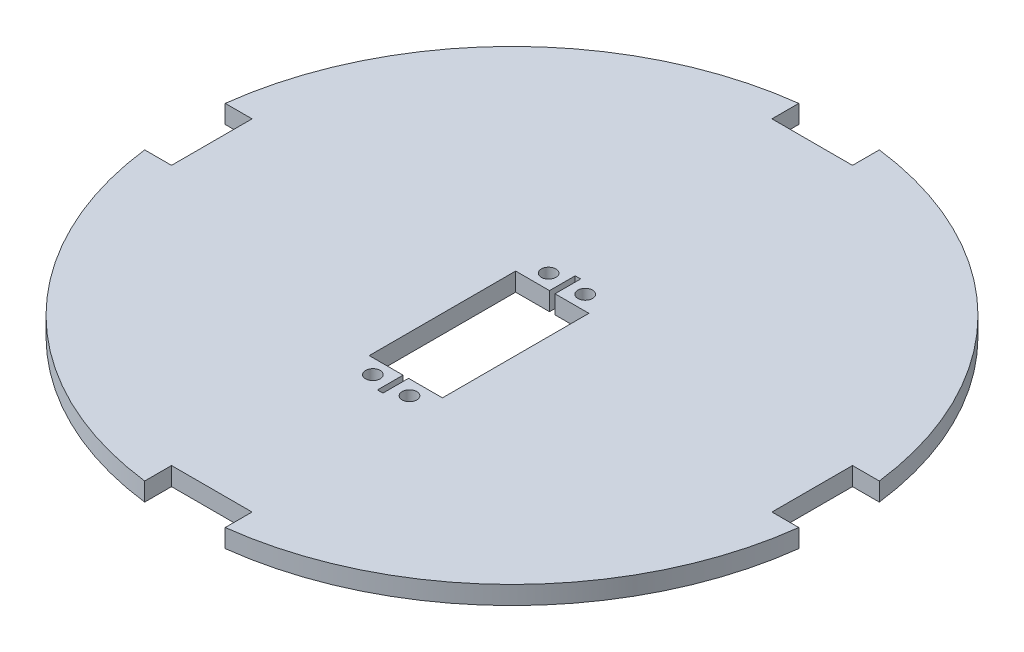
SolidWorks part; units mm, degrees
material "Balsa"
ref_plane "Front Plane" through (0, 0, 0) normal (0, 0, 1) x (1, 0, 0)
ref_plane "Top Plane" through (0, 0, 0) normal (0, 1, 0) x (1, 0, 0)
ref_plane "Right Plane" through (0, 0, 0) normal (1, 0, 0) x (0, 0, -1)
sketch "Sketch1" plane through (0, 0, 0) normal (0, 1, 0) x (1, 0, 0)
  circle A0 centre (0, 0) radius 90
  dimension "D1" = 180
extrude "Boss-Extrude1" add sketch "Sketch1" along normal blind 5
sketch "Sketch2" plane through (0, 5, 0) normal (0, 1, 0) x (1, 0, 0)
  line L1 (-11, 82) -> (11, 82)
  line L2 (-11, 82) -> (-11, 107.4856)
  line L3 (-11, 107.4856) -> (11, 107.4856)
  line L4 (11, 82) -> (11, 107.4856)
  line L5 (-11, 82) -> (11, 107.4856) construction
  line L6 (-11, 107.4856) -> (11, 82) construction
  point P0 (0, 94.7428)
  dimension "D1" = 82
  dimension "D2" = 22
extrude "Cut-Extrude1" cut sketch "Sketch2" against normal blind 10
pattern_circular "CirPattern3" count 4 over 360 about axis through (0, 0, 0) along (0, 1, 0) of "Cut-Extrude1"
sketch "Sketch3" plane through (0, 5, 0) normal (0, 1, 0) x (1, 0, 0)
  line L0 (-10, 11) -> (10, 11)
  line L1 (-10, 11) -> (-10, -29)
  line L2 (-10, -29) -> (10, -29)
  line L3 (10, 11) -> (10, -29)
  line L4 (-10, -9) -> (10, -9) construction
  line L5 (-0.75, 18) -> (0.75, 18)
  line L6 (-0.75, 18) -> (-0.75, 11)
  line L7 (-0.75, 11) -> (0.75, 11)
  line L8 (0.75, 18) -> (0.75, 11)
  line L9 (-0.75, -36) -> (0.75, -36)
  line L10 (-0.75, -36) -> (-0.75, -29)
  line L11 (0.75, -36) -> (0.75, -29)
  circle A0 centre (-5, 15) radius 2
  circle A1 centre (5, 15) radius 2
  circle A2 centre (5, -33) radius 2
  circle A3 centre (-5, -33) radius 2
  point P4 (0, 11)
  point P9 (0, 11)
  point P24 (0, 18)
  dimension "D6" = 4
  dimension "D7" = 4
  dimension "D1" = 20
  dimension "D2" = 40
  dimension "D3" = 7
  dimension "D4" = 1.5
  dimension "D5" = 10
  dimension "D8" = 5
  dimension "D9" = 24
  dimension "D10" = 18
extrude "Cut-Extrude2" cut sketch "Sketch3" against normal blind 10 contours L4 L1 L2 L3 | L9 L11 L2 L10 | A2 | A3 | L1 L4 L3 L0 | A0 | L8 L5 L6 L0 | A1
